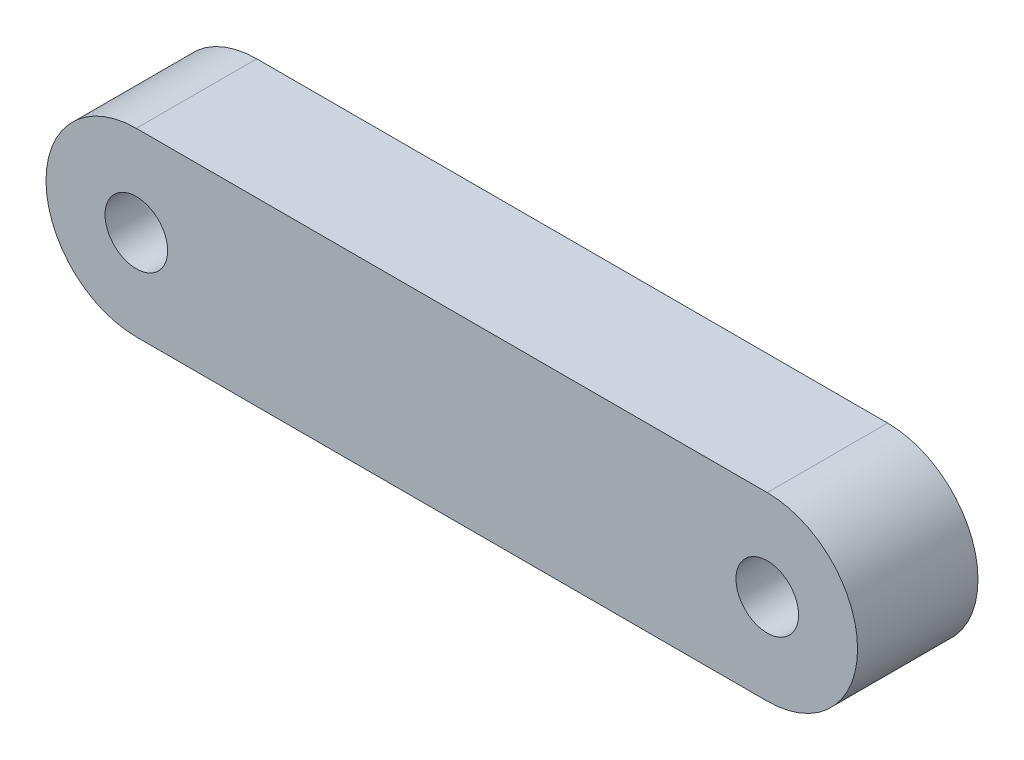
SolidWorks part; units mm, degrees
ref_plane "Front Plane" through (0, 0, 0) normal (0, 0, 1) x (1, 0, 0)
ref_plane "Top Plane" through (0, 0, 0) normal (0, 1, 0) x (1, 0, 0)
ref_plane "Right Plane" through (0, 0, 0) normal (1, 0, 0) x (0, 0, -1)
sketch "Sketch1" plane through (0, 0, 0) normal (0, 0, 1) x (1, 0, 0)
  line L0 (-16.6324, 0) -> (16.6324, 0) construction
  line L1 (-16.6324, 4.7625) -> (16.6324, 4.7625)
  line L2 (-16.6324, -4.7625) -> (16.6324, -4.7625)
  arc A0 (-16.6324, 4.7625) -> (-16.6324, -4.7625) centre (-16.6324, 0) ccw
  arc A1 (16.6324, -4.7625) -> (16.6324, 4.7625) centre (16.6324, 0) ccw
  circle A2 centre (16.6324, 0) radius 1.65
  circle A3 centre (-16.6324, 0) radius 1.65
  point P2 (0, 0)
  dimension "D1" = 42.7897
  dimension "D2" = 3.3
  dimension "D4" = 3.3
  dimension "D3" = 9.525
extrude "Boss-Extrude1" add sketch "Sketch1" along normal blind 6.35
sketch "Sketch2" plane through (0, 0, 0) normal (0, 0, -1) x (-1, 0, 0)
  line L0 (12.6726, 0) -> (16.6324, -3.9598)
  line L1 (20.5921, 3.9598) -> (12.6726, 3.9598)
  line L2 (20.5921, 3.9598) -> (20.5921, -3.9598)
  line L3 (20.5921, -3.9598) -> (12.6726, -3.9598)
  line L4 (12.6726, 3.9598) -> (12.6726, -3.9598)
  line L5 (16.6324, -3.9598) -> (16.6324, 3.9598) construction
  line L6 (20.5921, 0) -> (12.6726, 0) construction
  line L7 (16.6324, -3.9598) -> (20.5921, 0)
  line L8 (20.5921, 0) -> (16.6324, 3.9598)
  line L9 (16.6324, 3.9598) -> (12.6726, 0)
  point P0 (16.6324, 0)
  dimension "D1" = 5.6
extrude "Cut-Extrude1" cut sketch "Sketch2" against normal blind 2.1 contours L8 L9 L0 L7
fillet "Fillet1" radius 0.254 4 edges at (-16.6324, -3.9598, 1.05) (-12.6726, 0, 1.05) (-16.6324, 3.9598, 1.05) (-20.5921, 0, 1.05)
